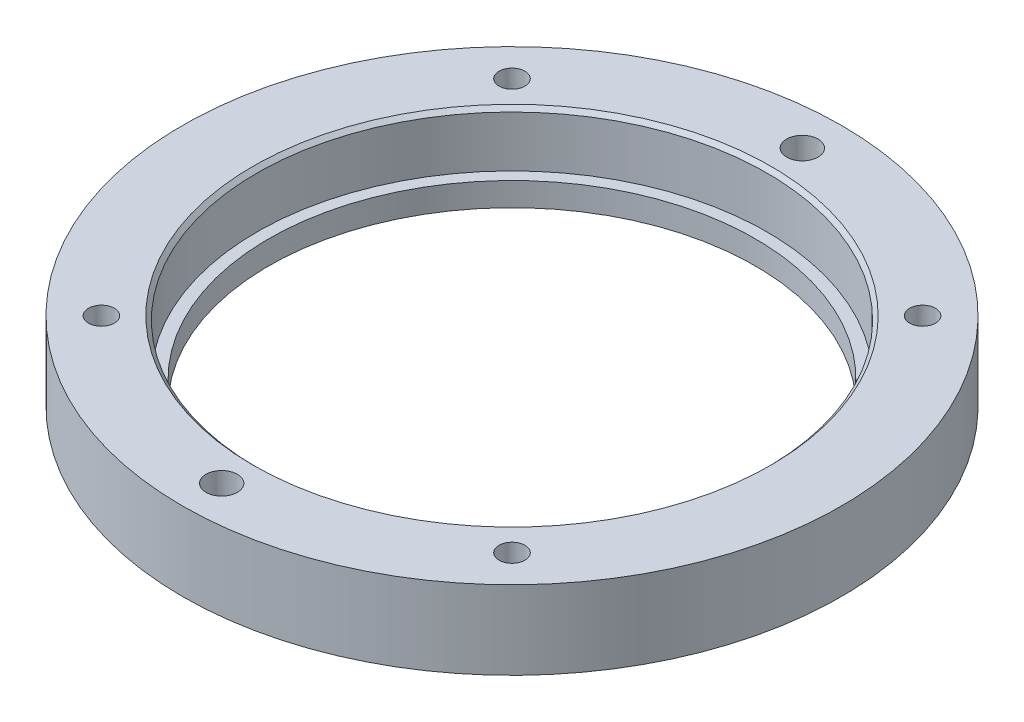
SolidWorks part; units mm, degrees
material "Alliage 1060"
ref_plane "Face" through (0, 0, 0) normal (0, 0, 1) x (1, 0, 0)
ref_plane "Dessus" through (0, 0, 0) normal (0, 1, 0) x (1, 0, 0)
ref_plane "Droite" through (0, 0, 0) normal (1, 0, 0) x (0, 0, -1)
sketch "Esquisse1" plane through (0, 0, 0) normal (1, 0, 0) x (0, 0, -1)
  line L0 (0, 0) -> (0, -70.5308) construction
  line L1 (-31, -3) -> (-31, 0)
  line L2 (-31, 0) -> (-32.5, 0)
  line L3 (-32.5, 0) -> (-32.5, 7)
  line L4 (-32.5, 7) -> (-42, 7)
  line L5 (-42, 7) -> (-42, -3)
  line L6 (-42, -3) -> (-31, -3)
  dimension "D1" = 65
  dimension "D2" = 10
  dimension "D3" = 84
  dimension "D4" = 7
  dimension "D5" = 62
revolve "Révolution1" add sketch "Esquisse1" angle 360 about L0
sketch "Esquisse5" plane through (0, 7, 0) normal (0, 1, 0) x (1, 0, 0)
  line L0 (0, 37) -> (0, -37) construction
  line L1 (-26.163, 26.163) -> (26.163, -26.163) construction
  circle A0 centre (0, 0) radius 37 construction
  dimension "D1" = 74
  dimension "D2" = 45
hole_wizard "Diamètre du perçage Ø4.0 (4)1" positions "Esquisse7" profile "Esquisse6" hole size "Ø4.0" standard "Din"
sketch "Esquisse7" plane through (0, 7, 0) normal (0, 1, 0) x (1, 0, 0)
  point P0 (0, 37)
  point P3 (0, -37)
sketch "Esquisse6" plane through (0, 7, -37) normal (1, 0, 0) x (0, 0, 1)
  line L0 (0, 0) -> (0, 6.2017)
  line L1 (0, 6.2017) -> (2, 5)
  line L2 (2, 5) -> (2, 0)
  line L5 (2, 0) -> (0, 0)
  line L10 (0, 6.2017) -> (-2, 5) construction
  line L11 (0, -6.35) -> (0, 107.95) construction
  dimension "Diamètre du perçage" = 4
  dimension "Profondeur du perçage" = 5
  dimension "Angle de pointe" = 118
hole_wizard "Trou taraudé M41" positions "Esquisse9" profile "Esquisse8" tap size "M4" standard "Iso" end condition up to next
sketch "Esquisse9" plane through (0, 7, 0) normal (0, 1, 0) x (1, 0, 0)
  point P0 (-26.163, 26.163)
sketch "Esquisse8" plane through (-26.163, 7, -26.163) normal (1, 0, 0) x (0, 0, 1)
  line L0 (0, 0) -> (0, 10.001)
  line L1 (0, 10.001) -> (1.65, 10.001)
  line L2 (1.65, 10.001) -> (1.65, 0)
  line L5 (1.65, 0) -> (0, 0)
  line L11 (0, -6.35) -> (0, 107.95) construction
  dimension "Diamètre du trou pour taraudage jusqu'au prochain" = 3.3
  dimension "Profondeur du trou pour taraudage jusqu'au prochain" = 10.001
cosmetic thread "Filetage de perçage1" parameters "D2"=4
pattern_circular "Répétition circulaire1" count 4 every 90 about axis through (0, 0, 0) along (0, 1, 0) of "Trou taraudé M41"
chamfer "Chanfrein1" distance 0.5 angle 45 1 edges at (0, 7, 32.5)
